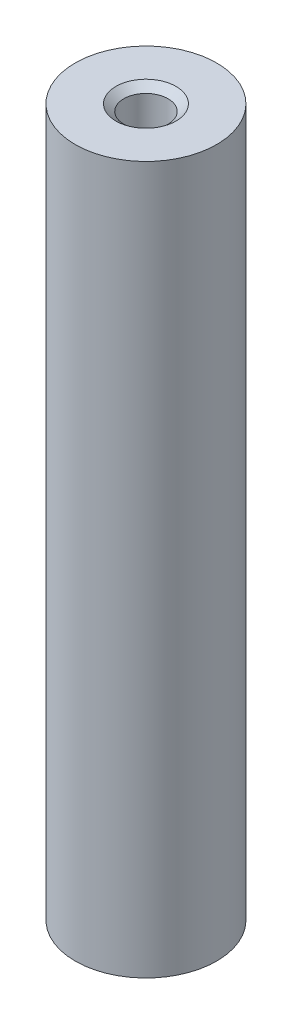
SolidWorks part; units mm, degrees
material "AISI 304"
ref_plane "Front" through (0, 0, 0) normal (0, 0, 1) x (1, 0, 0)
ref_plane "Top" through (0, 0, 0) normal (0, 1, 0) x (1, 0, 0)
ref_plane "Right" through (0, 0, 0) normal (1, 0, 0) x (0, 0, -1)
sketch "Sketch1" plane through (0, 0, 0) normal (0, 1, 0) x (1, 0, 0)
  circle A0 centre (0, 0) radius 12.7
  dimension "D1" = 25.4
extrude "Boss-Extrude1" add sketch "Sketch1" along normal blind 127
hole_wizard "1/2-13 Tapped Hole1" positions "Sketch2" profile "Sketch3" tap size "1/2-13" standard "ANSI Inch"
sketch "Sketch2" plane through (0, 0, 0) normal (0, -1, 0) x (-1, 0, 0)
  point P0 (0, 0)
sketch "Sketch3" plane through (0, 0, 0) normal (1, 0, 0) x (0, 0, -1)
  line L0 (0, 0) -> (0, 28.6195)
  line L1 (0, 28.6195) -> (5.3581, 25.4)
  line L2 (5.3581, 25.4) -> (5.3581, 1.3651)
  line L3 (5.3581, 1.3651) -> (6.985, 0)
  line L5 (6.985, 0) -> (0, 0)
  line L6 (-5.3581, 1.3651) -> (-6.985, 0) construction
  line L10 (0, 28.6195) -> (-5.3581, 25.4) construction
  line L11 (0, -6.35) -> (0, 107.95) construction
  dimension "Tap Drill Dia." = 10.7163
  dimension "Tap Drill Depth" = 25.4
  dimension "Near C'Sink Dia." = 13.97
  dimension "Near C'Sink Angle" = 100
  dimension "Drill Angle" = 118
cosmetic thread "Hole Thread1"
hole_wizard "3/8-16 Tapped Hole1" positions "Sketch4" profile "Sketch5" tap size "3/8-16" standard "ANSI Inch"
sketch "Sketch4" plane through (0, 127, 0) normal (0, 1, 0) x (1, 0, 0)
  point P0 (0, 0)
sketch "Sketch5" plane through (0, 127, 0) normal (1, 0, 0) x (0, 0, 1)
  line L0 (0, 0) -> (0, 27.7847)
  line L1 (0, 27.7847) -> (3.9687, 25.4)
  line L2 (3.9687, 25.4) -> (3.9687, 1.1989)
  line L3 (3.9687, 1.1989) -> (5.3975, 0)
  line L5 (5.3975, 0) -> (0, 0)
  line L6 (-3.9687, 1.1989) -> (-5.3975, 0) construction
  line L10 (0, 27.7847) -> (-3.9688, 25.4) construction
  line L11 (0, -6.35) -> (0, 107.95) construction
  dimension "Tap Drill Dia." = 7.9375
  dimension "Tap Drill Depth" = 25.4
  dimension "Near C'Sink Dia." = 10.795
  dimension "Near C'Sink Angle" = 100
  dimension "Drill Angle" = 118
cosmetic thread "Hole Thread2"
